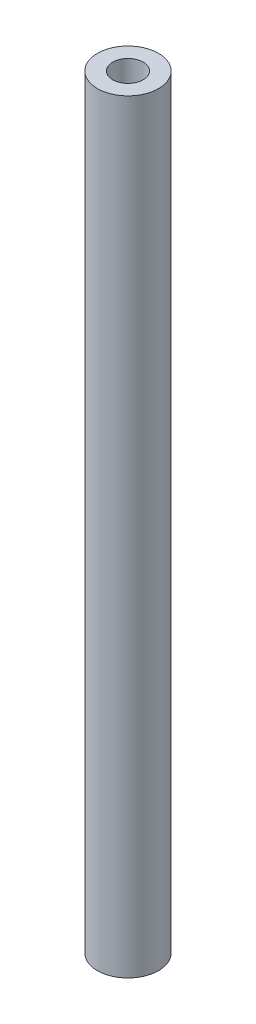
SolidWorks part; units mm, degrees
ref_plane "Front Plane" through (0, 0, 0) normal (0, 0, 1) x (1, 0, 0)
ref_plane "Top Plane" through (0, 0, 0) normal (0, 1, 0) x (1, 0, 0)
ref_plane "Right Plane" through (0, 0, 0) normal (1, 0, 0) x (0, 0, -1)
sketch "Sketch1" plane through (0, 0, 0) normal (0, 1, 0) x (1, 0, 0)
  circle A0 centre (0, 0) radius 1
  circle A1 centre (0, 0) radius 2
  dimension "D1" = 2
  dimension "D2" = 4
extrude "Boss-Extrude1" add sketch "Sketch1" along normal mid plane 50
